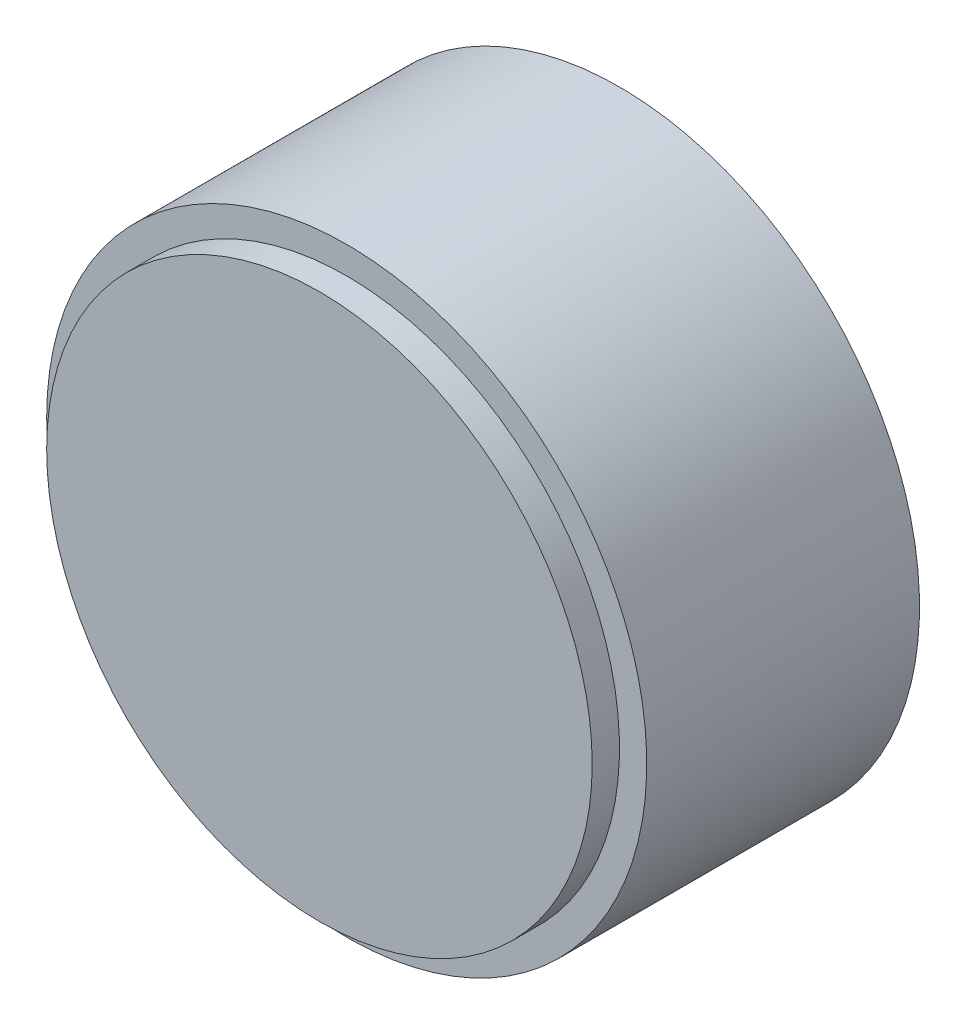
SolidWorks part; units mm, degrees
ref_plane "Plan de face" through (0, 0, 0) normal (0, 0, 1) x (1, 0, 0)
ref_plane "Plan de dessus" through (0, 0, 0) normal (0, 1, 0) x (1, 0, 0)
ref_plane "Plan de droite" through (0, 0, 0) normal (1, 0, 0) x (0, 0, -1)
sketch "Esquisse1" plane through (0, 0, 0) normal (0, 0, 1) x (1, 0, 0)
  circle A0 centre (0, 0) radius 30
  point P14 (0, 0)
  dimension "D1" = 60
extrude "Boss.-Extru.1" add sketch "Esquisse1" along normal blind 35
sketch "Esquisse2" plane through (0, 0, 0) normal (0, 0, -1) x (-1, 0, 0)
  circle A0 centre (0, 8) radius 2
  circle A1 centre (8, 0) radius 2
  circle A2 centre (0, -8) radius 2
  circle A3 centre (-8, 0) radius 2
  circle A4 centre (0, 0) radius 2
  point P12 (0, 0)
  dimension "D1" = 4
  dimension "D4" = 4
  dimension "D2" = 8
  dimension "D3" = 4
extrude "Enlèv. mat.-Extru.1" cut sketch "Esquisse2" against normal blind 10
sketch "Esquisse3" plane through (0, 0, 0) normal (0, 0, -1) x (-1, 0, 0)
  circle A2 centre (0, 0) radius 30 construction
  circle A3 centre (0, 0) radius 33
  circle A4 centre (0, 0) radius 33
  circle A5 centre (0, 0) radius 30
  dimension "D1" = 3
extrude "Boss.-Extru.2" add sketch "Esquisse3" against normal blind 30 from offset 2
